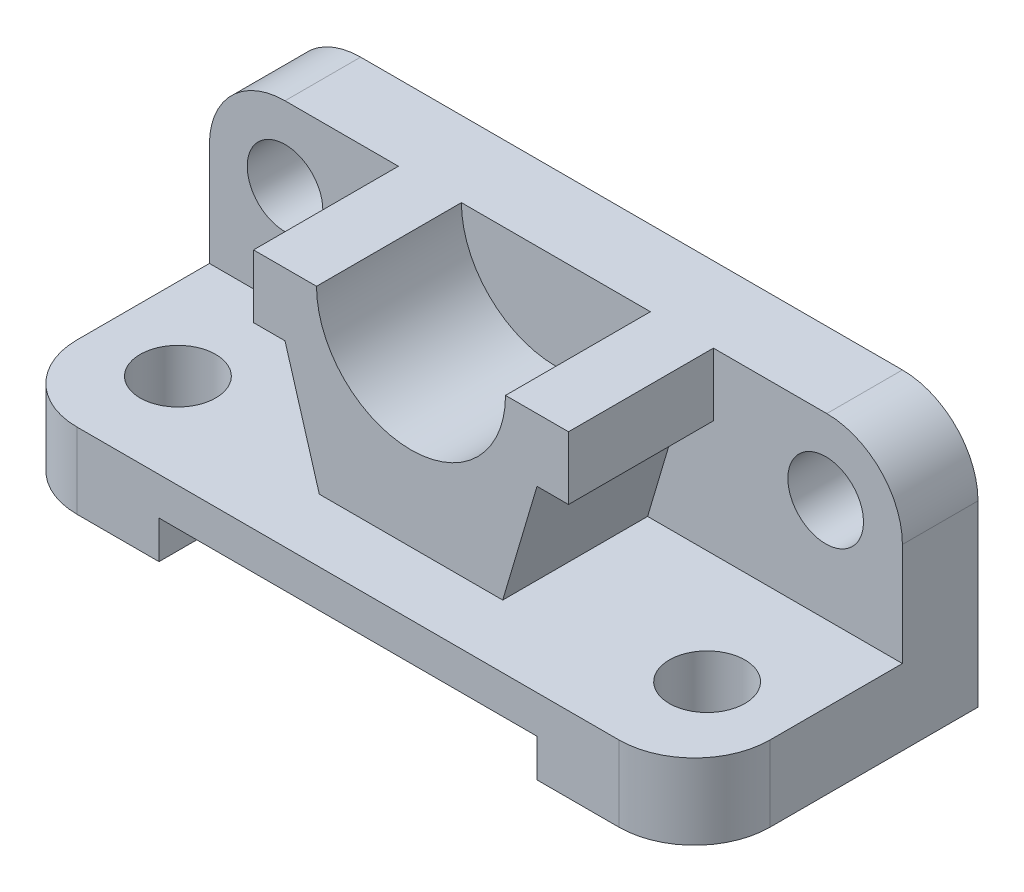
SolidWorks part; units mm, degrees
ref_plane "Front Plane" through (0, 0, 0) normal (0, 0, 1) x (1, 0, 0)
ref_plane "Top Plane" through (0, 0, 0) normal (0, 1, 0) x (1, 0, 0)
ref_plane "Right Plane" through (0, 0, 0) normal (1, 0, 0) x (0, 0, -1)
sketch "Sketch1" plane through (0, 0, 0) normal (0, 1, 0) x (1, 0, 0)
  line L1 (-55, 22.5) -> (55, 22.5)
  line L2 (-55, 22.5) -> (-55, -22.5)
  line L3 (-55, -22.5) -> (55, -22.5)
  line L4 (55, 22.5) -> (55, -22.5)
  line L5 (-55, 22.5) -> (55, -22.5) construction
  line L6 (-55, -22.5) -> (55, 22.5) construction
  point P0 (0, 0)
  dimension "D1" = 110
  dimension "D2" = 45
extrude "Boss-Extrude1" add sketch "Sketch1" along normal blind 12
fillet "Fillet1" radius 12 2 edges at (-55, 6, 22.5) (55, 6, 22.5)
sketch "Sketch2" plane through (0, 0, -22.5) normal (0, 0, -1) x (-1, 0, 0)
  line L0 (0, 0) -> (0, 78.0807) construction
  line L1 (-55, 12) -> (55, 12)
  line L2 (-55, 12) -> (-55, 40.361)
  line L3 (-55, 40.361) -> (55, 40.361)
  line L4 (55, 12) -> (55, 40.361)
extrude "Boss-Extrude2" add sketch "Sketch2" against normal blind 12
fillet "Fillet2" radius 12 2 edges at (-55, 40.361, -16.5) (55, 40.361, -16.5)
sketch "Sketch3" plane through (0, 0, -10.5) normal (0, 0, 1) x (1, 0, 0)
  line L0 (0, 0) -> (0, 62.257) construction
  line L1 (-43, 40.361) -> (43, 40.361) construction
  line L2 (15, 40.361) -> (25, 40.361)
  line L3 (25, 40.361) -> (25, 30.361)
  line L4 (25, 30.361) -> (20, 30.361)
  line L5 (20, 30.361) -> (11, 0)
  line L6 (-43, 0) -> (43, 0) construction
  line L7 (11, 0) -> (-11, 0)
  line L8 (-11, 0) -> (-20, 30.361)
  line L9 (-20, 30.361) -> (-25, 30.361)
  line L10 (-25, 30.361) -> (-25, 40.361)
  line L11 (-25, 40.361) -> (-15, 40.361)
  arc A0 (-15, 40.361) -> (15, 40.361) centre (0, 40.361) ccw
  point P14 (0, 0)
  dimension "D8" = 15
  dimension "D1" = 10
  dimension "D2" = 10
  dimension "D3" = 5
  dimension "D4" = 10
  dimension "D5" = 10
  dimension "D6" = 5
  dimension "D7" = 22
extrude "Boss-Extrude3" add sketch "Sketch3" along normal blind 23
sketch "Sketch4" plane through (0, 12, 0) normal (0, 1, 0) x (1, 0, 0)
  line L0 (55, -10.5) -> (55, 10.5) construction
  line L1 (-55, 10.5) -> (-55, -10.5) construction
  line L3 (-43, -22.5) -> (43, -22.5) construction
  circle A0 centre (-42, -7.5) radius 6
  circle A1 centre (42, -7.5) radius 6
  point P10 (-35.617, -22.5)
  dimension "D1" = 12
  dimension "D2" = 13
  dimension "D3" = 13
  dimension "D4" = 15
  dimension "D5" = 15
extrude "Cut-Extrude1" cut sketch "Sketch4" against normal through all
sketch "Sketch5" plane through (0, 0, -10.5) normal (0, 0, 1) x (1, 0, 0)
  line L2 (-0.0897, 0.0331) -> (-0.0897, 59.7836) construction
  circle A0 centre (-43, 28.361) radius 6
  circle A1 centre (42.8206, 28.361) radius 6
  arc A2 (-43, 40.361) -> (-55, 28.361) centre (-43, 28.361) ccw construction
  point P2 (-43.7576, 28.8412)
  dimension "D1" = 12
extrude "Cut-Extrude2" cut sketch "Sketch5" against normal through all
sketch "Sketch6" plane through (0, 0, 22.5) normal (0, 0, 1) x (1, 0, 0)
  line L0 (-43, 0) -> (43, 0) construction
  line L1 (-30, 0) -> (30, 0)
  line L2 (-30, 0) -> (-30, 6)
  line L3 (-30, 6) -> (30, 6)
  line L4 (30, 0) -> (30, 6)
  point P6 (0, 0)
  dimension "D1" = 60
  dimension "D2" = 6
extrude "Cut-Extrude3" cut sketch "Sketch6" against normal through all
